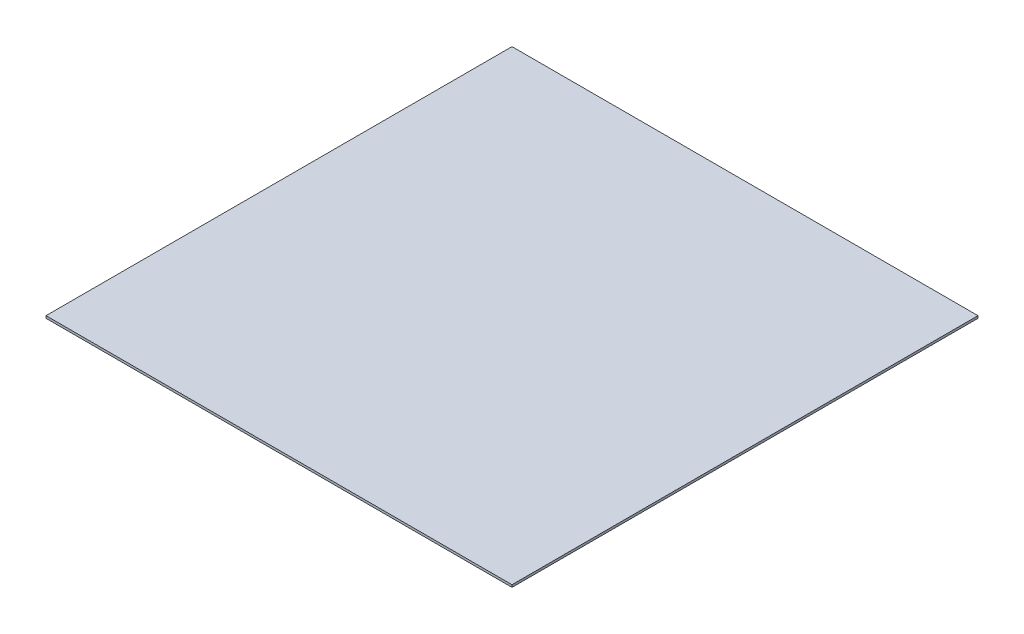
SolidWorks part; units mm, degrees
ref_plane "前视基准面" through (0, 0, 0) normal (0, 0, 1) x (1, 0, 0)
ref_plane "上视基准面" through (0, 0, 0) normal (0, 1, 0) x (1, 0, 0)
ref_plane "右视基准面" through (0, 0, 0) normal (1, 0, 0) x (0, 0, -1)
sketch "草图1" plane through (0, 0, 0) normal (0, 1, 0) x (1, 0, 0)
  line L5 (-200, -200) -> (200, -200)
  line L6 (-200, -200) -> (-200, 200)
  line L7 (-200, 200) -> (200, 200)
  line L8 (200, -200) -> (200, 200)
  line L9 (-200, -200) -> (200, 200) construction
  line L10 (-200, 200) -> (200, -200) construction
  point P0 (0, 0)
  dimension "D1" = 400
extrude "凸台-拉伸1" add sketch "草图1" along normal mid plane 2
